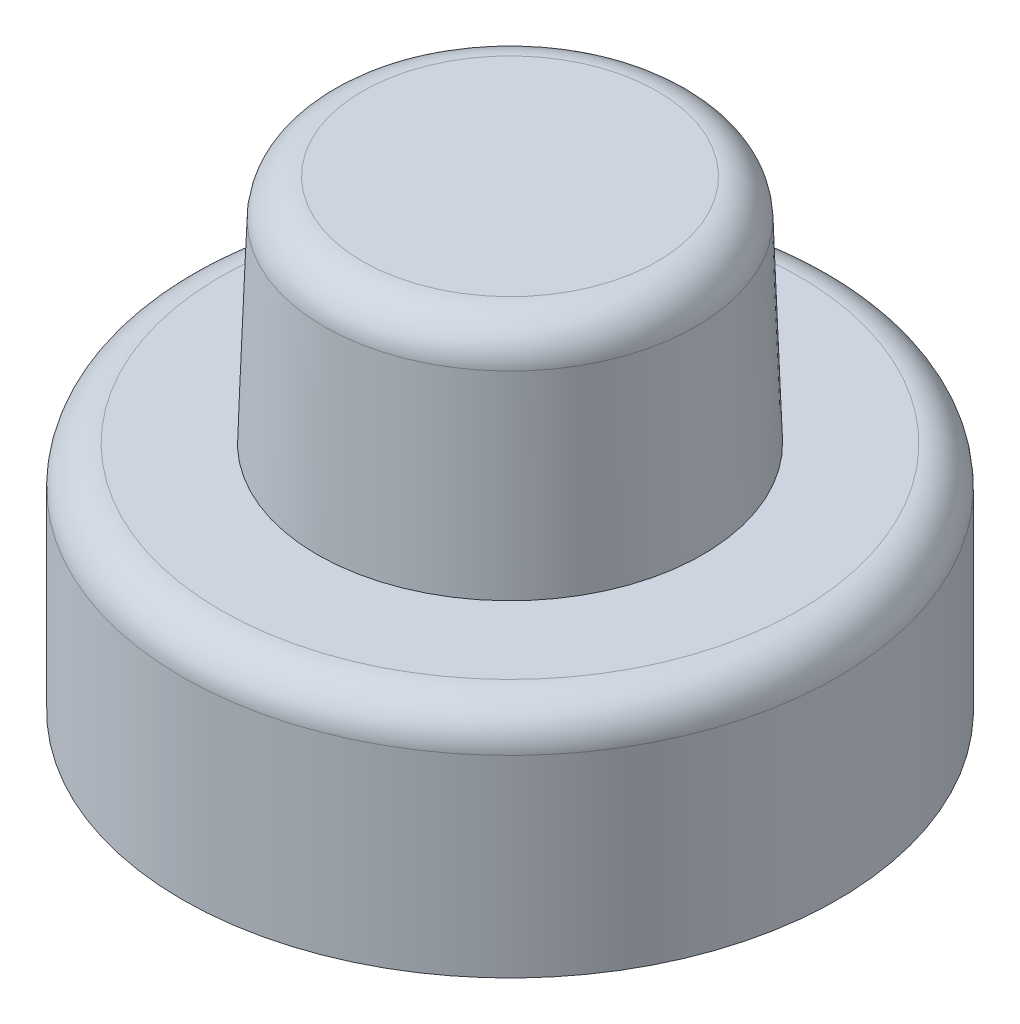
SolidWorks part; units mm, degrees
ref_plane "Front Plane" through (0, 0, 0) normal (0, 0, 1) x (1, 0, 0)
ref_plane "Top Plane" through (0, 0, 0) normal (0, 1, 0) x (1, 0, 0)
ref_plane "Right Plane" through (0, 0, 0) normal (1, 0, 0) x (0, 0, -1)
sketch "Sketch1" plane through (0, 0, 0) normal (0, 1, 0) x (1, 0, 0)
  circle A0 centre (-51.1202, 0) radius 8.5
extrude "Boss-Extrude1" add sketch "Sketch1" along normal blind 6
sketch "Sketch2" plane through (0, 6, 0) normal (0, 1, 0) x (1, 0, 0)
  circle A0 centre (-51.1202, 0) radius 5
  circle A1 centre (-51.1202, 0) radius 8.5 construction
fillet "Fillet2" radius 1 1 edges at (-51.1202, 6, 8.5)
extrude "Boss-Extrude3" add sketch "Sketch2" along normal blind 6 draft 2 contours A0
fillet "Fillet4" radius 1 1 edges at (-51.1202, 12, 4.7905)
equation "\".5.00mm\"=1"
